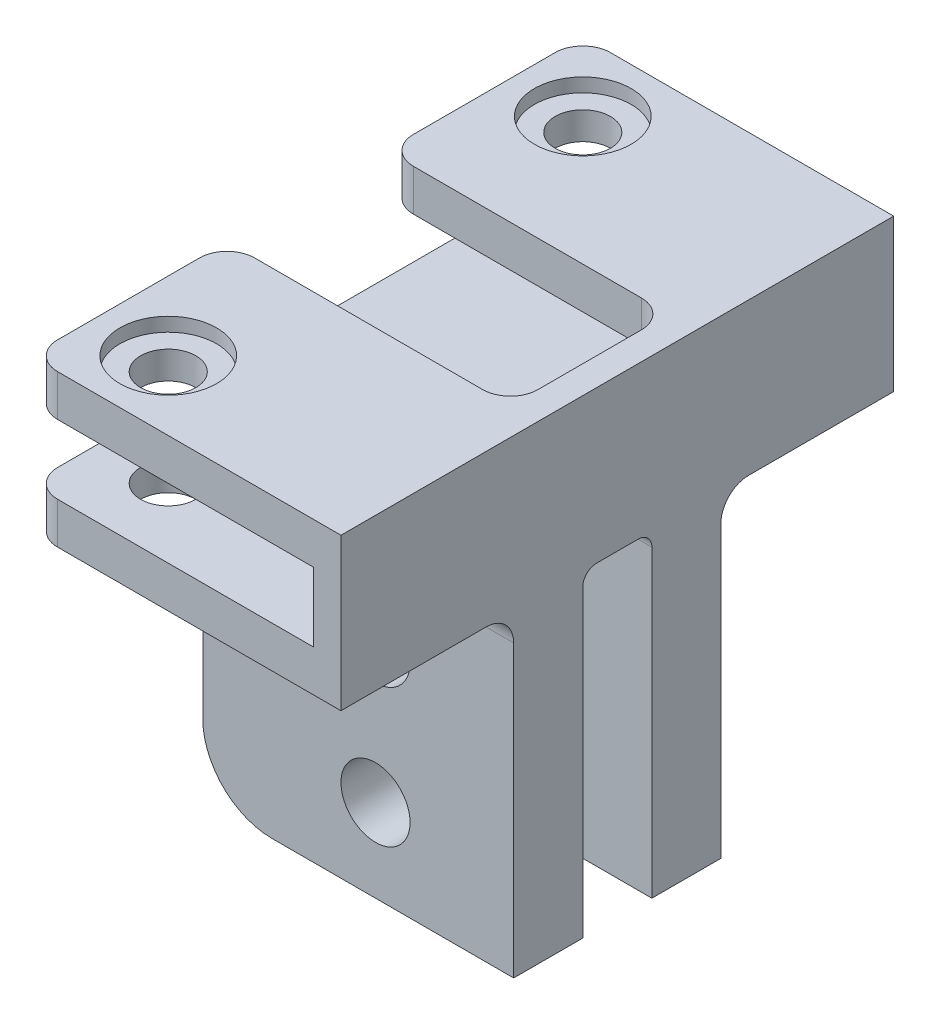
SolidWorks part; units mm, degrees
ref_plane "Front Plane" through (0, 0, 0) normal (0, 0, 1) x (1, 0, 0)
ref_plane "Top Plane" through (0, 0, 0) normal (0, 1, 0) x (1, 0, 0)
ref_plane "Right Plane" through (0, 0, 0) normal (1, 0, 0) x (0, 0, -1)
sketch "Sketch2" plane through (0, 0, 0) normal (0, 0, 1) x (1, 0, 0)
  line L2 (10, 31) -> (0, 31)
  line L3 (10, 31) -> (10, 52)
  line L4 (10, 52) -> (0, 52)
  line L5 (0, 31) -> (0, 52)
  circle A0 centre (5, 47) radius 2.5
  circle A1 centre (5, 37) radius 2.5
extrude "Boss-Extrude1" add sketch "Sketch2" along normal blind 5
sketch "Sketch3" plane through (0, 0, 0) normal (0, 0, -1) x (-1, 0, 0)
  line L4 (-10, 52) -> (-10, 31)
  line L5 (-10, 31) -> (0, 31)
  line L6 (0, 31) -> (0, 52)
  line L7 (0, 52) -> (-10, 52)
  line L8 (-10, 52) -> (-10, 31)
  line L9 (-10, 31) -> (0, 31)
  line L10 (0, 31) -> (0, 52)
  line L11 (0, 52) -> (-10, 52)
  circle A0 centre (-5, 37) radius 2.5
  circle A1 centre (-5, 47) radius 2.5
  dimension "D1" = 0
extrude "Boss-Extrude3" add sketch "Sketch3" along normal blind 5 from offset 5 separate body
sketch "Sketch4" plane through (0, 52, 0) normal (0, 1, 0) x (1, 0, 0)
  line L4 (10, 0) -> (0, 0)
  line L5 (0, 0) -> (0, -5)
  line L6 (0, -5) -> (10, -5)
  line L7 (10, -5) -> (10, 0)
  line L8 (10, 0) -> (0, 0)
  line L9 (0, 0) -> (0, -5)
  line L10 (0, -5) -> (10, -5)
  line L11 (10, -5) -> (10, 0)
  dimension "D1" = 0
extrude "Boss-Extrude4" add sketch "Sketch4" along normal blind 2
sketch "Sketch5" plane through (0, 52, 0) normal (0, 1, 0) x (1, 0, 0)
  line L4 (0, 5) -> (10, 5)
  line L5 (10, 5) -> (10, 10)
  line L6 (10, 10) -> (0, 10)
  line L7 (0, 10) -> (0, 5)
  line L8 (0, 5) -> (10, 5)
  line L9 (10, 5) -> (10, 10)
  line L10 (10, 10) -> (0, 10)
  line L11 (0, 10) -> (0, 5)
  dimension "D1" = 0
extrude "Boss-Extrude5" add sketch "Sketch5" along normal blind 2
sketch "Sketch6" plane through (0, 54, 0) normal (0, 1, 0) x (1, 0, 0)
  line L0 (10, -5) -> (10, -17.5)
  line L2 (0, -5) -> (0, 10)
  line L4 (10, -5) -> (10, 10)
  line L5 (10, -17.5) -> (0, -17.5)
  line L6 (0, -17.5) -> (0, -5)
  line L7 (10, 10) -> (10, 22.5)
  line L8 (10, 22.5) -> (0, 22.5)
  line L9 (0, 22.5) -> (0, 10)
  dimension "D1" = 12.5
  dimension "D2" = 12.5
extrude "Boss-Extrude6" add sketch "Sketch6" along normal blind 3
fillet "Fillet1" radius 1 2 edges at (5, 54, -5) (5, 54, 0)
fillet "Fillet2" radius 2 2 edges at (5, 54, -10) (5, 54, 5)
sketch "Sketch7" plane through (0, 57, 0) normal (0, 1, 0) x (1, 0, 0)
  line L0 (10, 22.5) -> (0, -17.5) construction
  line L1 (5, 2.5) -> (15, 2.5) construction
  dimension "D1" = 10
sketch "Sketch8" plane through (10, 0, 0) normal (1, 0, 0) x (0, 0, -1)
  line L12 (0, 31) -> (0, 53)
  line L13 (1, 54) -> (4, 54)
  line L14 (5, 53) -> (5, 31)
  line L15 (5, 31) -> (10, 31)
  line L16 (10, 31) -> (10, 52)
  line L17 (12, 54) -> (22.5, 54)
  line L18 (22.5, 54) -> (22.5, 57)
  line L19 (22.5, 57) -> (-17.5, 57)
  line L20 (-17.5, 57) -> (-17.5, 54)
  line L21 (-17.5, 54) -> (-7, 54)
  line L22 (-5, 52) -> (-5, 31)
  line L23 (-5, 31) -> (0, 31)
  line L24 (0, 31) -> (0, 53)
  line L25 (1, 54) -> (4, 54)
  line L26 (5, 53) -> (5, 31)
  line L27 (5, 31) -> (10, 31)
  line L28 (10, 31) -> (10, 52)
  line L29 (12, 54) -> (22.5, 54)
  line L30 (22.5, 54) -> (22.5, 57)
  line L31 (22.5, 57) -> (-17.5, 57)
  line L32 (-17.5, 57) -> (-17.5, 54)
  line L33 (-17.5, 54) -> (-7, 54)
  line L34 (-5, 52) -> (-5, 31)
  line L35 (-5, 31) -> (0, 31)
  arc A4 (1, 54) -> (0, 53) centre (1, 53) ccw
  arc A5 (5, 53) -> (4, 54) centre (4, 53) ccw
  arc A6 (12, 54) -> (10, 52) centre (12, 52) ccw
  arc A7 (-5, 52) -> (-7, 54) centre (-7, 52) ccw
  arc A8 (1, 54) -> (0, 53) centre (1, 53) ccw
  arc A9 (5, 53) -> (4, 54) centre (4, 53) ccw
  arc A10 (12, 54) -> (10, 52) centre (12, 52) ccw
  arc A11 (-5, 52) -> (-7, 54) centre (-7, 52) ccw
  dimension "D1" = 0
extrude "Boss-Extrude7" add sketch "Sketch8" along normal blind 5
sketch "Sketch9" plane through (0, 57, 0) normal (0, 1, 0) x (1, 0, 0)
  line L0 (0, -17.5) -> (15, -17.5) construction
  line L1 (15, 22.5) -> (13, 22.5)
  line L2 (15, 22.5) -> (15, -17.5)
  line L3 (15, -17.5) -> (13, -17.5)
  line L4 (13, 22.5) -> (13, -17.5)
  dimension "D1" = 2
extrude "Boss-Extrude8" add sketch "Sketch9" along normal blind 5
sketch "Sketch10" plane through (0, 62, 0) normal (0, 1, 0) x (1, 0, 0)
  line L1 (15, 22.5) -> (0, 22.5)
  line L2 (15, 22.5) -> (15, -17.5)
  line L3 (15, -17.5) -> (0, -17.5)
  line L4 (0, 22.5) -> (0, -17.5)
extrude "Boss-Extrude9" add sketch "Sketch10" along normal blind 3
sketch "Sketch12" plane through (0, 65, 0) normal (0, 1, 0) x (1, 0, 0)
  line L0 (15, -17.5) -> (0, 22.5) construction
  line L1 (7.5, 2.5) -> (7.5, -3) construction
  line L2 (15, -17.5) -> (15, 22.5) construction
  line L3 (13, 8.2438) -> (2, 8.2438)
  line L4 (13, 8.2438) -> (13, -3.2438)
  line L5 (13, -3.2438) -> (2, -3.2438)
  line L7 (13, 8.2438) -> (2, -3.2438) construction
  line L8 (13, -3.2438) -> (2, 8.2438) construction
  line L9 (2, 8.2438) -> (0, 8.2438)
  line L10 (0, 22.5) -> (0, -17.5) construction
  line L11 (0, 8.2438) -> (0, -3.2438)
  line L12 (0, -3.2438) -> (2, -3.2438)
  dimension "D1" = 5.5
  dimension "D2" = 2
extrude "Cut-Extrude1" cut sketch "Sketch12" against normal blind 3
sketch "Sketch13" plane through (0, 0, 0) normal (-1, 0, 0) x (0, 0, 1)
  line L0 (17.5, 65) -> (3.2438, 65) construction
  line L1 (3.2438, 65) -> (3.2438, 62) construction
  line L2 (3.2438, 62) -> (17.5, 62) construction
  line L3 (17.5, 62) -> (17.5, 65) construction
  line L4 (-22.5, 62) -> (-8.2438, 62) construction
  line L5 (-8.2438, 62) -> (-8.2438, 65) construction
  line L6 (-8.2438, 65) -> (-22.5, 65) construction
  line L7 (-22.5, 65) -> (-22.5, 62) construction
  line L8 (17.5, 65) -> (3.2438, 65)
  line L9 (3.2438, 65) -> (3.2438, 62)
  line L10 (3.2438, 62) -> (17.5, 62)
  line L11 (17.5, 62) -> (17.5, 65)
  line L12 (-4, 54) -> (-1, 54)
  line L13 (0, 53) -> (0, 31)
  line L14 (0, 31) -> (5, 31)
  line L15 (5, 31) -> (5, 52)
  line L16 (7, 54) -> (17.5, 54)
  line L17 (17.5, 54) -> (17.5, 57)
  line L18 (17.5, 57) -> (-22.5, 57)
  line L19 (-22.5, 57) -> (-22.5, 54)
  line L20 (-22.5, 54) -> (-12, 54)
  line L21 (-10, 52) -> (-10, 31)
  line L22 (-10, 31) -> (-5, 31)
  line L23 (-5, 31) -> (-5, 53)
  line L24 (-4, 54) -> (-1, 54)
  line L25 (0, 53) -> (0, 31)
  line L26 (0, 31) -> (5, 31)
  line L27 (5, 31) -> (5, 52)
  line L28 (7, 54) -> (17.5, 54)
  line L29 (17.5, 54) -> (17.5, 57)
  line L30 (17.5, 57) -> (-22.5, 57)
  line L31 (-22.5, 57) -> (-22.5, 54)
  line L32 (-22.5, 54) -> (-12, 54)
  line L33 (-10, 52) -> (-10, 31)
  line L34 (-10, 31) -> (-5, 31)
  line L35 (-5, 31) -> (-5, 53)
  line L36 (-22.5, 62) -> (-8.2438, 62)
  line L37 (-8.2438, 62) -> (-8.2438, 65)
  line L38 (-8.2438, 65) -> (-22.5, 65)
  line L39 (-22.5, 65) -> (-22.5, 62)
  arc A4 (0, 53) -> (-1, 54) centre (-1, 53) ccw
  arc A5 (7, 54) -> (5, 52) centre (7, 52) ccw
  arc A6 (-10, 52) -> (-12, 54) centre (-12, 52) ccw
  arc A7 (-4, 54) -> (-5, 53) centre (-4, 53) ccw
  arc A8 (0, 53) -> (-1, 54) centre (-1, 53) ccw
  arc A9 (7, 54) -> (5, 52) centre (7, 52) ccw
  arc A10 (-10, 52) -> (-12, 54) centre (-12, 52) ccw
  arc A11 (-4, 54) -> (-5, 53) centre (-4, 53) ccw
  dimension "D1" = 0
extrude "Boss-Extrude10" add sketch "Sketch13" along normal blind 7.5
sketch "Sketch14" plane through (0, 65, 0) normal (0, 1, 0) x (1, 0, 0)
  line L0 (-7.5, -17.5) -> (15, -17.5) construction
  line L1 (-7.5, -17.5) -> (-7.5, -3.2438) construction
  line L2 (-7.5, 8.2438) -> (-7.5, 22.5) construction
  line L3 (15, 22.5) -> (-7.5, 22.5) construction
  circle A0 centre (-2.5, -12.5) radius 2
  circle A1 centre (-2.5, 17.5) radius 2
  dimension "D1" = 4
  dimension "D2" = 4
  dimension "D3" = 5
  dimension "D4" = 5
  dimension "D5" = 5
  dimension "D6" = 5
extrude "Cut-Extrude2" cut sketch "Sketch14" against normal through all
sketch "Sketch15" plane through (0, 65, 0) normal (0, 1, 0) x (1, 0, 0)
  circle A0 centre (-2.5, 17.5) radius 3.5
  circle A1 centre (-2.5, -12.5) radius 3.5
  dimension "D1" = 7
  dimension "D2" = 7
extrude "Cut-Extrude3" cut sketch "Sketch15" against normal blind 1
sketch "Sketch16" plane through (0, 54, 0) normal (0, -1, 0) x (1, 0, 0)
  line L0 (-7.5, 7) -> (-7.5, 17.5) construction
  line L1 (-6.75, 14.9537) -> (-6.75, 10.0463)
  line L2 (-6.75, 10.0463) -> (-2.5, 7.5925)
  line L3 (-2.5, 7.5925) -> (1.75, 10.0463)
  line L4 (1.75, 10.0463) -> (1.75, 14.9537)
  line L5 (1.75, 14.9537) -> (-2.5, 17.4075)
  line L6 (-2.5, 17.4075) -> (-6.75, 14.9537)
  circle A0 centre (-2.5, 12.5) radius 4.25 construction
  dimension "D1" = 8.5
extrude "Cut-Extrude4" cut sketch "Sketch16" against normal blind 1
sketch "Sketch17" plane through (0, 54, 0) normal (0, -1, 0) x (-1, 0, 0)
  line L0 (7.5, 22.5) -> (7.5, 12) construction
  line L1 (6.75, 15.0463) -> (6.75, 19.9537)
  line L2 (6.75, 19.9537) -> (2.5, 22.4075)
  line L3 (2.5, 22.4075) -> (-1.75, 19.9537)
  line L4 (-1.75, 19.9537) -> (-1.75, 15.0463)
  line L5 (-1.75, 15.0463) -> (2.5, 12.5925)
  line L6 (2.5, 12.5925) -> (6.75, 15.0463)
  circle A0 centre (2.5, 17.5) radius 4.25 construction
  dimension "D1" = 8.5
extrude "Cut-Extrude5" cut sketch "Sketch17" against normal blind 1
fillet "Fillet3" radius 5 2 edges at (-7.5, 31, 2.5) (-7.5, 31, -7.5)
fillet "Fillet4" radius 2 6 edges at (-7.5, 63.5, -8.2438) (-7.5, 63.5, 3.2438) (-7.5, 55.5, 17.5) (-7.5, 63.5, 17.5) (-7.5, 55.5, -22.5) (-7.5, 63.5, -22.5)
fillet "Fillet5" radius 2 2 edges at (13, 63.5, 3.2438) (13, 63.5, -8.2438)
